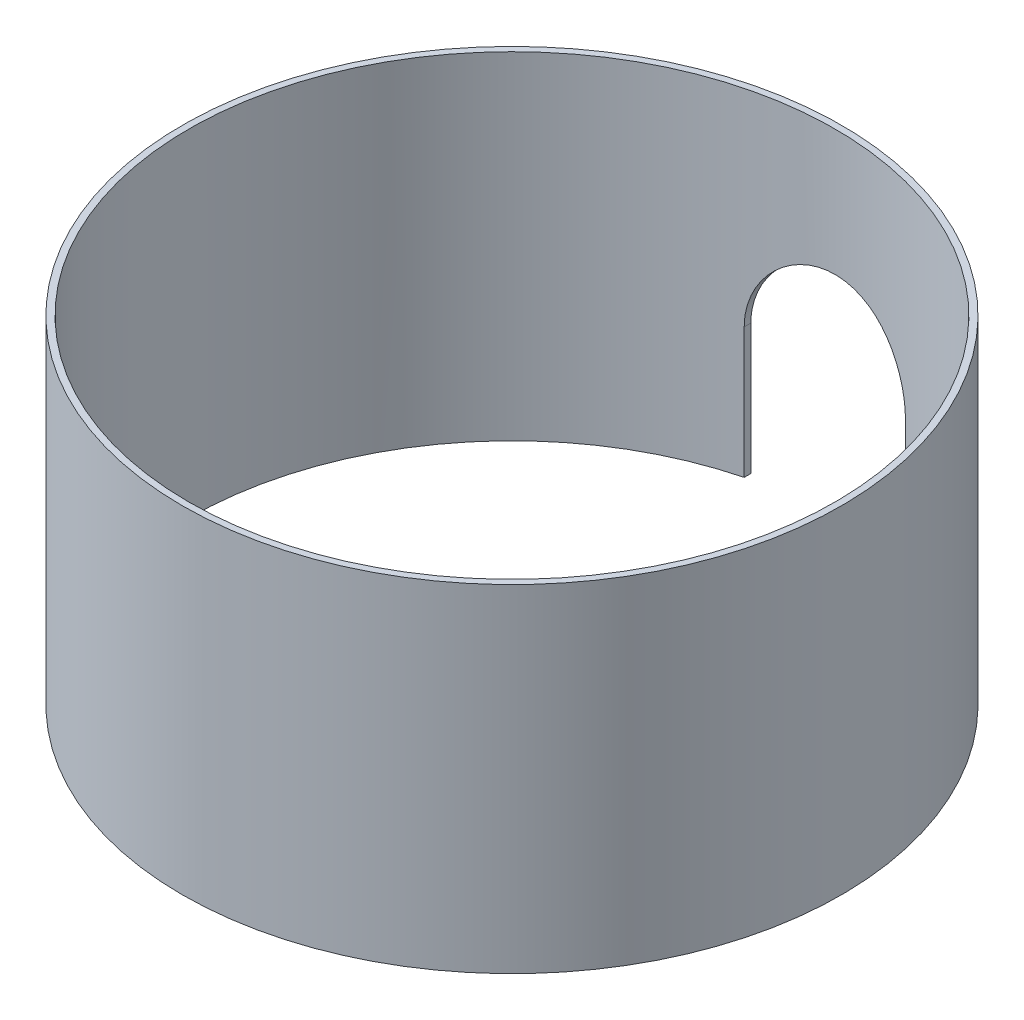
SolidWorks part; units mm, degrees
material "PTFE (general)"
ref_plane "Front Plane" through (0, 0, 0) normal (0, 0, 1) x (1, 0, 0)
ref_plane "Top Plane" through (0, 0, 0) normal (0, 1, 0) x (1, 0, 0)
ref_plane "Right Plane" through (0, 0, 0) normal (1, 0, 0) x (0, 0, -1)
sketch "Sketch1" plane through (0, 0, 0) normal (0, 1, 0) x (1, 0, 0)
  circle A0 centre (-43.8588, -17.1756) radius 51.838
  circle A1 centre (-43.8588, -17.1756) radius 50.822
extrude "Boss-Extrude1" add sketch "Sketch1" along normal blind 54
sketch "Sketch2" plane through (0, 0, 0) normal (0, 0, 1) x (1, 0, 0)
  line L0 (-43.7515, 33.1815) -> (-43.8502, 40.9369) construction
  line L6 (-43.8588, 0) -> (-43.8588, 50.3848) construction
  line L7 (-95.6968, 0) -> (7.9792, 0) construction
  line L8 (-56.5408, 20.5) -> (-56.5408, -11.1334)
  line L9 (-56.5408, -11.1334) -> (-31.1768, -11.1334)
  line L10 (-31.1768, -11.1334) -> (-31.1768, 20.5)
  arc A0 (-31.1768, 20.5) -> (-56.5408, 20.5) centre (-43.8588, 20.5) ccw
  dimension "D2" = 25.364
extrude "Cut-Extrude1" cut sketch "Sketch2" against normal blind 53
sketch "Sketch3" plane through (0, 54, 0) normal (0, 1, 0) x (1, 0, 0)
  circle A0 centre (-43.8588, -17.1756) radius 50.822
  circle A1 centre (-43.8588, -17.1756) radius 51.838
extrude "Cut-Extrude2" cut sketch "Sketch3" against normal blind 1
